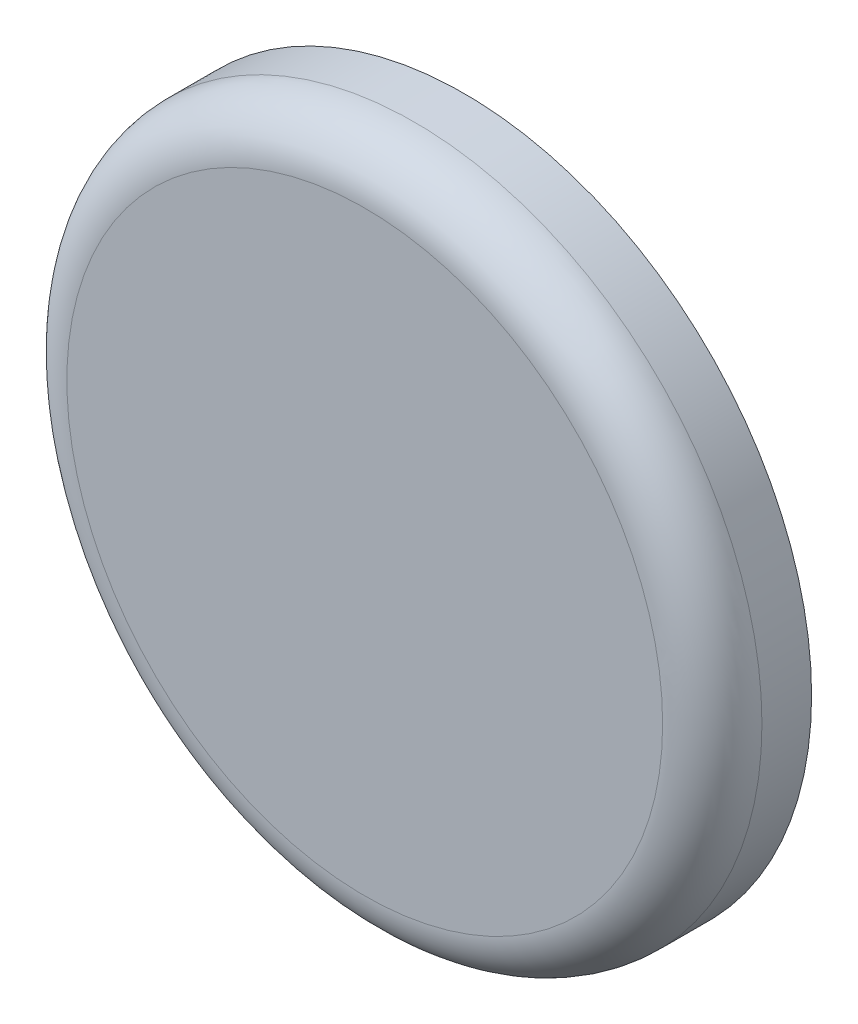
SolidWorks part; units mm, degrees
ref_plane "Спереди" through (0, 0, 0) normal (0, 0, 1) x (1, 0, 0)
ref_plane "Сверху" through (0, 0, 0) normal (0, 1, 0) x (1, 0, 0)
ref_plane "Справа" through (0, 0, 0) normal (1, 0, 0) x (0, 0, -1)
sketch "Эскиз1" plane through (0, 0, 0) normal (0, 0, 1) x (1, 0, 0)
  circle A0 centre (0, 0) radius 7
  dimension "D1" = 14
extrude "Бобышка-Вытянуть1" add sketch "Эскиз1" along normal blind 2
fillet "Скругление1" radius 1 1 edges at (7, 0, 2)
